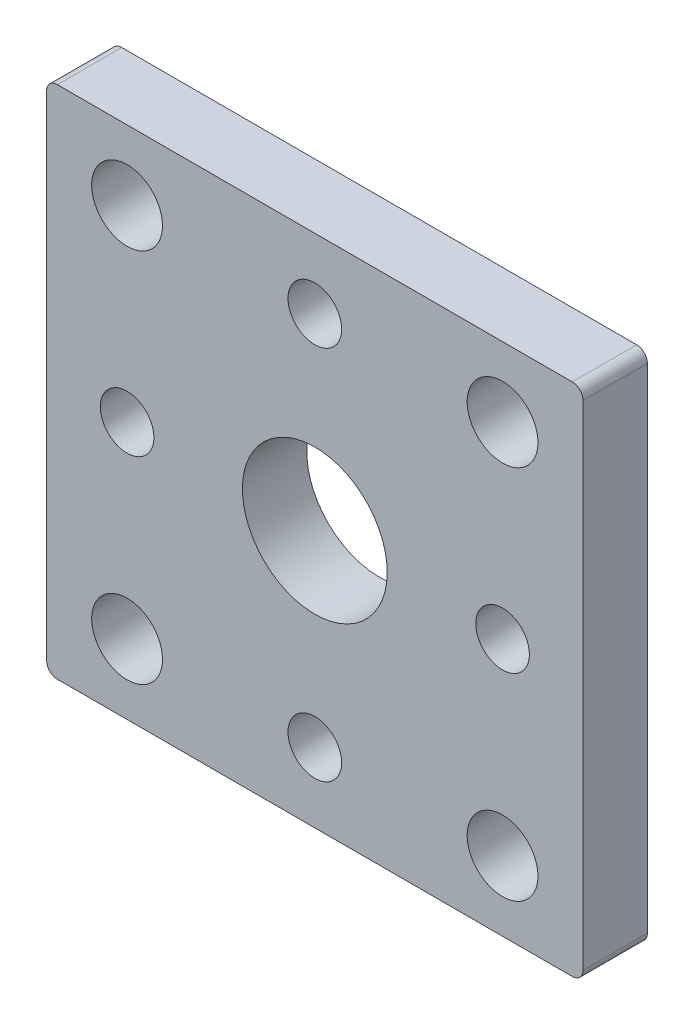
SolidWorks part; units mm, degrees
ref_plane "前视基准面" through (0, 0, 0) normal (0, 0, 1) x (1, 0, 0)
ref_plane "上视基准面" through (0, 0, 0) normal (0, 1, 0) x (1, 0, 0)
ref_plane "右视基准面" through (0, 0, 0) normal (1, 0, 0) x (0, 0, -1)
other "Configuration Table"
sketch "草图1" plane through (0, 0, 0) normal (0, 0, 1) x (1, 0, 0)
  line L0 (0, 0) -> (50, 0)
  line L1 (50, 0) -> (50, -48)
  line L2 (50, -48) -> (0, -48)
  line L3 (0, -48) -> (0, 0)
  dimension "D1" = 50
  dimension "D2" = 48
extrude "凸台-拉伸1" add sketch "草图1" along normal blind 6
sketch "草图2" plane through (0, 0, 6) normal (0, 0, 1) x (1, 0, 0)
  line L0 (50, -24) -> (0, -24)
  line L1 (50, -48) -> (50, 0) construction
  line L2 (0, 0) -> (0, -48) construction
  line L3 (25, 0) -> (25, -48)
  line L4 (50, 0) -> (0, 0) construction
  line L5 (0, -48) -> (50, -48) construction
  line L6 (25, -24) -> (25, -12)
  circle A0 centre (42.5, -6.5) radius 3.3
  circle A1 centre (42.5, -41.5) radius 3.3
  circle A2 centre (7.5, -41.5) radius 3.3
  circle A3 centre (7.5, -6.5) radius 3.3
  circle A4 centre (25, -24) radius 6.75
  dimension "D1" = 17.5
  dimension "D3" = 6.6
  dimension "D4" = 13.5
  dimension "D2" = 17.5
fillet "圆角1" radius 1 4 edges at (50, -48, 3) (0, -48, 3) (0, 0, 3) (50, 0, 3)
sketch "草图8" plane through (0, 0, 6) normal (0, 0, 1) x (1, 0, 0)
  line L5 (25, -48) -> (25, 0)
  line L6 (1, -48) -> (49, -48) construction
  line L7 (49, 0) -> (1, 0) construction
  line L8 (50, -24) -> (0, -24)
  line L9 (50, -47) -> (50, -1) construction
  line L10 (0, -1) -> (0, -47) construction
  line L11 (25, -24) -> (55, -24)
  line L12 (25, -24) -> (-5, -24)
  circle A0 centre (-5, -24) radius 3.3648
  circle A1 centre (25, -24) radius 3.7667
  circle A2 centre (55, -24) radius 3.2192
  circle A3 centre (40, -24) radius 3.2586
  circle A4 centre (10, -24) radius 3.1199
  dimension "D3" = 15
  dimension "D1" = 30
  dimension "D2" = 60
  dimension "D4" = 15
extrude "切除-拉伸1" cut sketch "草图2" against normal through all contours A3 | A0 | A1 | A2 | L0 A4 L6 | L6 A4 L0 | L0 A4 L3 | L3 A4 L0
sketch "草图9" plane through (0, 0, 6) normal (0, 0, 1) x (1, 0, 0)
  line L0 (50, -24) -> (0, -24)
  line L1 (50, -47) -> (50, -1) construction
  line L2 (0, -1) -> (0, -47) construction
  line L3 (25, -48) -> (25, 0)
  line L4 (1, -48) -> (49, -48) construction
  line L5 (49, 0) -> (1, 0) construction
  circle A0 centre (25, -6.5) radius 3
  circle A1 centre (42.5, -24) radius 3
  circle A2 centre (25, -41.5) radius 3
  circle A3 centre (7.5, -24) radius 3
  point P15 (25, -24)
  point P23 (25, -24)
  dimension "D1" = 4
  dimension "D2" = 17.5
hole_wizard "M6 螺纹孔2" positions "草图10" profile "草图11" tap size "M6" standard "GB" end condition through all
sketch "草图10" plane through (0, 0, 6) normal (0, 0, 1) x (1, 0, 0)
  point P0 (25, -6.5)
  point P3 (42.5, -24)
  point P6 (25, -41.5)
  point P9 (7.5, -24)
sketch "草图11" plane through (25, -6.5, 6) normal (1, 0, 0) x (0, -1, 0)
  line L0 (0, 0) -> (0, 6)
  line L1 (0, 6) -> (2.5, 6)
  line L2 (2.5, 6) -> (2.5, 0)
  line L5 (2.5, 0) -> (0, 0)
  line L11 (0, -6.35) -> (0, 107.95) construction
  dimension "通孔螺纹孔钻头直径" = 5
  dimension "通孔螺纹孔钻头深度" = 6
cosmetic thread "孔螺蚊线1" parameters "D2"=6
cosmetic thread "孔螺蚊线2" parameters "D2"=6
cosmetic thread "孔螺蚊线3" parameters "D2"=6
cosmetic thread "孔螺蚊线4" parameters "D2"=6
